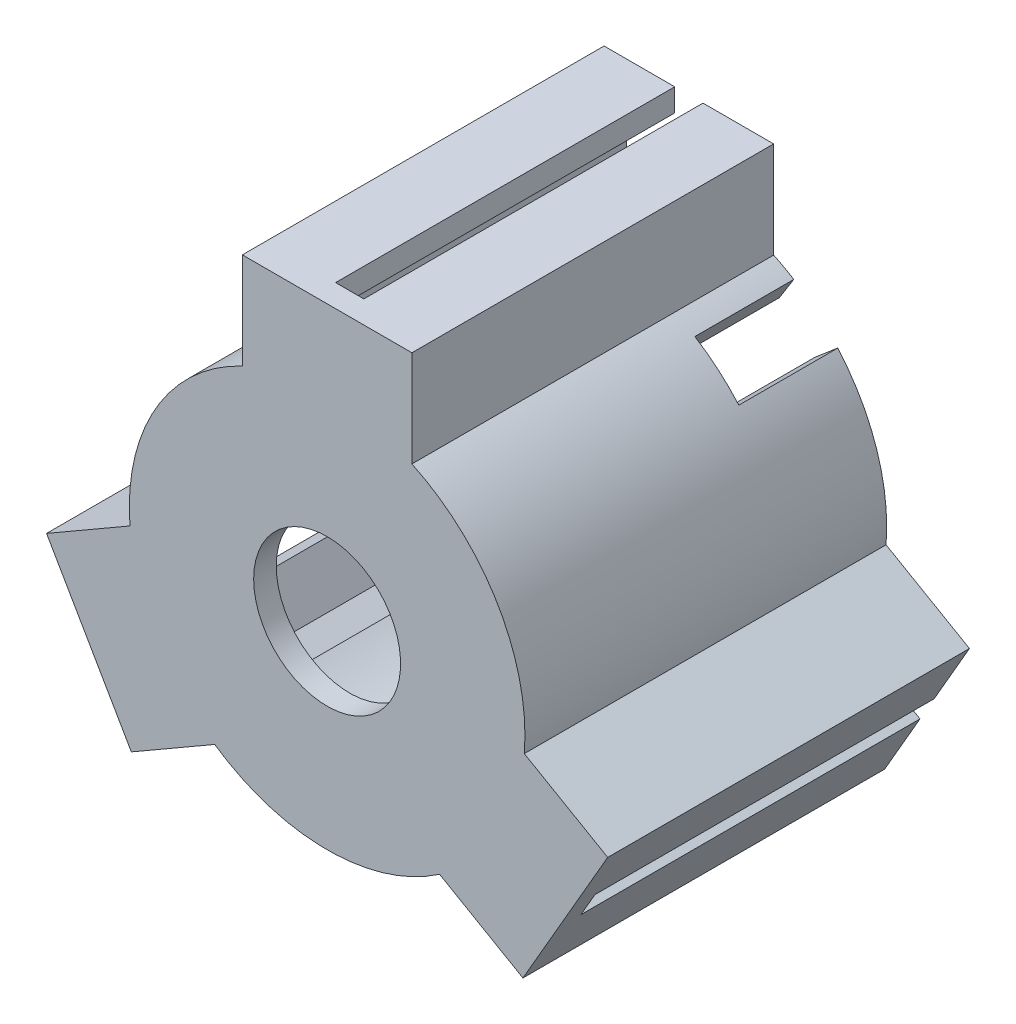
SolidWorks part; units mm, degrees
ref_plane "Alzado" through (0, 0, 0) normal (0, 0, 1) x (1, 0, 0)
ref_plane "Planta" through (0, 0, 0) normal (0, 1, 0) x (1, 0, 0)
ref_plane "Vista lateral" through (0, 0, 0) normal (1, 0, 0) x (0, 0, -1)
sketch "Croquis1" plane through (0, 0, 0) normal (0, 0, 1) x (1, 0, 0)
  line L0 (-64.0406, 19.4171) -> (-64.0406, 22.8246)
  line L1 (-64.0406, 22.8246) -> (-58.0406, 22.8246)
  line L2 (-58.0406, 22.8246) -> (-58.0406, 19.4171)
  line L3 (-54.0634, 12.5284) -> (-51.1124, 10.8246)
  line L4 (-51.1124, 10.8246) -> (-54.1124, 5.6285)
  line L5 (-54.1124, 5.6285) -> (-57.0634, 7.3322)
  line L6 (-65.0178, 7.3322) -> (-67.9688, 5.6285)
  line L7 (-67.9688, 5.6285) -> (-70.9688, 10.8246)
  line L8 (-70.9688, 10.8246) -> (-68.0178, 12.5284)
  arc A1 (-68.0178, 12.5284) -> (-64.0406, 19.4171) centre (-61.0406, 13.0926) cw
  arc A2 (-58.0406, 19.4171) -> (-54.0634, 12.5284) centre (-61.0406, 13.0926) cw
  arc A3 (-57.0634, 7.3322) -> (-65.0178, 7.3322) centre (-61.0406, 13.0926) cw
  dimension "D2" = 6
  dimension "D4" = 120
  dimension "D6" = 120
  dimension "D7" = 6
  dimension "D8" = 6
extrude "Saliente-Extruir1" add sketch "Croquis1" along normal blind 0.8
sketch "Croquis2" plane through (0, 0, 0) normal (0, 0, -1) x (-1, 0, 0)
  line L0 (69.7188, 8.6596) -> (70.9688, 10.8246)
  line L1 (70.9688, 10.8246) -> (68.0178, 12.5284)
  line L2 (70.9688, 10.8246) -> (67.9688, 5.6285) construction
  line L3 (69.7188, 8.6596) -> (69.026, 9.0596)
  line L4 (69.026, 9.0596) -> (69.876, 10.5318)
  line L5 (69.876, 10.5318) -> (67.1047, 12.1318)
  line L6 (65.0178, 7.3322) -> (67.9688, 5.6285)
  line L7 (67.9688, 5.6285) -> (69.2188, 7.7935)
  line L8 (69.2188, 7.7935) -> (68.5245, 8.1944)
  line L9 (68.5245, 8.1944) -> (67.6745, 6.7222)
  line L10 (67.6745, 6.7222) -> (64.9032, 8.3222)
  line L11 (52.8624, 7.7935) -> (54.1124, 5.6285)
  line L13 (54.1124, 5.6285) -> (57.0634, 7.3322)
  line L14 (52.8624, 7.7935) -> (53.5552, 8.1935)
  line L15 (53.5552, 8.1935) -> (54.4052, 6.7213)
  line L16 (54.4052, 6.7213) -> (57.1765, 8.3213)
  line L17 (54.0634, 12.5284) -> (51.1124, 10.8246)
  line L18 (51.1124, 10.8246) -> (52.3624, 8.6596)
  line L19 (52.3624, 8.6596) -> (53.0567, 9.0604)
  line L20 (53.0567, 9.0604) -> (52.2067, 10.5327)
  line L21 (52.2067, 10.5327) -> (54.978, 12.1327)
  line L22 (60.5406, 22.8246) -> (58.0406, 22.8246)
  line L23 (58.0406, 22.8246) -> (58.0406, 19.4171)
  line L24 (60.5406, 22.8246) -> (60.5406, 22.0246)
  line L25 (60.5406, 22.0246) -> (58.8406, 22.0246)
  line L26 (58.8406, 22.0246) -> (58.8406, 18.8246)
  line L27 (64.0406, 19.4171) -> (64.0406, 22.8246)
  line L28 (64.0406, 22.8246) -> (61.5406, 22.8246)
  line L29 (61.5406, 22.8246) -> (61.5406, 22.0229)
  line L30 (61.5406, 22.0229) -> (63.2406, 22.0229)
  line L31 (63.2406, 22.0229) -> (63.2406, 18.8229)
  arc A0 (65.0178, 7.3322) -> (57.0634, 7.3322) centre (61.0406, 13.0926) cw
  arc A1 (57.1765, 8.3213) -> (64.9032, 8.3222) centre (61.0392, 14.1591) ccw
  arc A2 (54.0634, 12.5284) -> (58.0406, 19.4171) centre (61.0406, 13.0926) cw
  arc A3 (58.8406, 18.8246) -> (54.978, 12.1327) centre (61.9649, 12.5605) ccw
  arc A4 (64.0406, 19.4171) -> (68.0178, 12.5284) centre (61.0406, 13.0926) cw
  arc A5 (67.1047, 12.1318) -> (63.2406, 18.8229) centre (60.1177, 12.5581) ccw
  point P53 (61.0406, 13.0926)
  dimension "D3" = 3
  dimension "D6" = 3.2
  dimension "D13" = 7
  dimension "D1" = 0.8
  dimension "D2" = 0.8
  dimension "D4" = 0.8017
  dimension "D5" = 3.2
  dimension "D7" = 0.8
  dimension "D8" = 0.8
  dimension "D9" = 1
  dimension "D10" = 2.5
  dimension "D11" = 3.4075
extrude "Saliente-Extruir2" add sketch "Croquis2" along normal blind 12
sketch "Croquis3" plane through (0, 0, 0) normal (0, 0, -1) x (-1, 0, 0)
  circle A0 centre (61.0406, 13.0926) radius 2.6
extrude "Cortar-Extruir1" cut sketch "Croquis3" against normal up to vertex (0.8 mm away)
sketch "Croquis4" plane through (0, 0, -12) normal (0, 0, -1) x (-1, 0, 0)
  line L0 (57.8372, 18.214) -> (57.3285, 19.0272)
  line L1 (56.5729, 17.0244) -> (55.773, 17.7025)
  line L2 (67.0776, 13.3061) -> (68.0362, 13.34)
  line L3 (66.6795, 14.9958) -> (67.6668, 15.3495)
  line L4 (58.207, 7.7576) -> (57.7571, 6.9105)
  line L5 (59.8694, 7.2575) -> (59.6821, 6.2257)
  arc A0 (55.773, 17.7025) -> (57.3285, 19.0272) centre (61.0406, 13.0926) cw
  arc A1 (58.0406, 19.4171) -> (54.0634, 12.5284) centre (61.0406, 13.0926) ccw construction
  arc A2 (58.8406, 18.8246) -> (54.978, 12.1327) centre (61.9649, 12.5605) ccw construction
  arc A3 (57.8372, 18.214) -> (56.5729, 17.0244) centre (61.9649, 12.5605) ccw
  arc A4 (67.6668, 15.3495) -> (68.0362, 13.34) centre (61.0406, 13.0926) cw
  arc A5 (67.0776, 13.3061) -> (66.6795, 14.9958) centre (60.1177, 12.5581) ccw
  arc A6 (59.6821, 6.2257) -> (57.7571, 6.9105) centre (61.0406, 13.0926) cw
  arc A7 (58.207, 7.7576) -> (59.8694, 7.2575) centre (61.0392, 14.1591) ccw
  point P25 (61.0406, 13.0926)
  dimension "D1" = 3
extrude "Cortar-Extruir2" cut sketch "Croquis4" against normal blind 3.5
